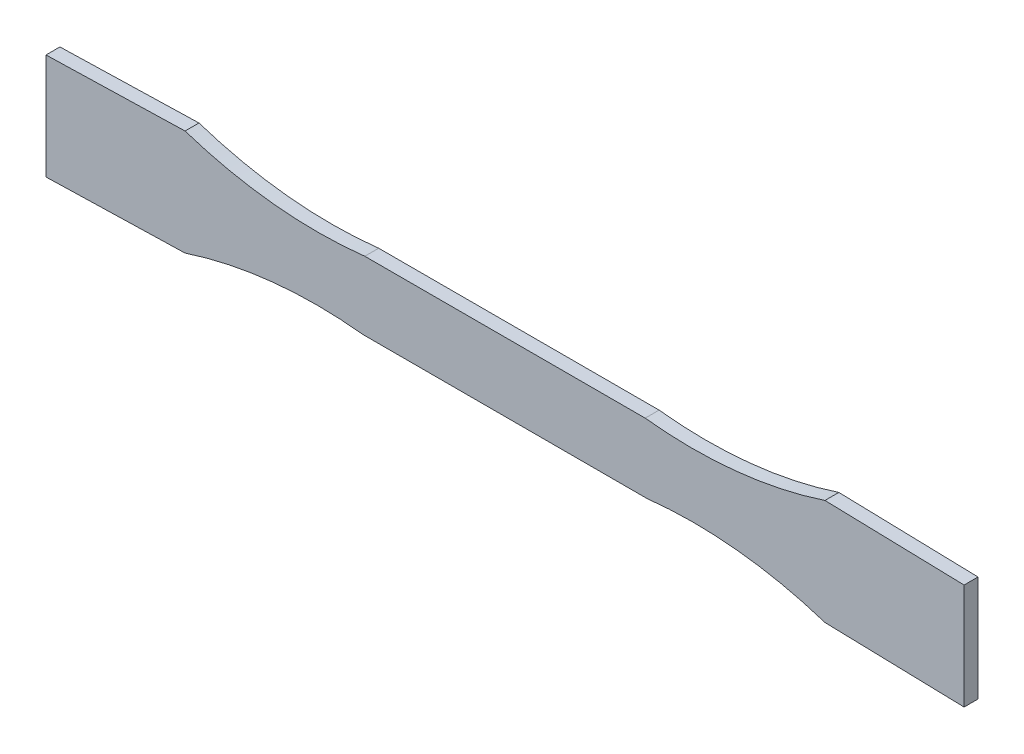
SolidWorks part; units mm, degrees
ref_plane "Front Plane" through (0, 0, 0) normal (0, 0, 1) x (1, 0, 0)
ref_plane "Top Plane" through (0, 0, 0) normal (0, 1, 0) x (1, 0, 0)
ref_plane "Right Plane" through (0, 0, 0) normal (1, 0, 0) x (0, 0, -1)
sketch "Sketch2" plane through (0, 0, 0) normal (0, 0, 1) x (1, 0, 0)
  line L0 (-46.6281, 0) -> (118.3719, 0) construction
  line L9 (-46.6174, 8.5394) -> (-46.6174, -10.4606)
  line L19 (-46.6174, -10.4606) -> (-21.626, -9.8028)
  line L21 (-46.6174, 8.5394) -> (-46.6174, -10.4606)
  line L22 (-46.6174, 8.5394) -> (-21.626, 9.1972)
  line L23 (10.676, 5.8556) -> (61.0678, 5.8556)
  line L24 (10.3532, -6.4946) -> (61.3906, -6.4946)
  line L25 (118.3826, 8.5394) -> (118.3826, -10.4606)
  line L26 (118.3826, -10.4606) -> (93.3913, -9.8028)
  line L27 (118.3826, 8.5394) -> (93.374, 9.1972)
  arc A0 (-21.626, 9.1972) -> (10.676, 5.8556) centre (2.1647, 81.3775) ccw
  arc A1 (-21.626, -9.8028) -> (10.3532, -6.4946) centre (2.007, -82.0349) cw
  arc A6 (93.3913, -9.8028) -> (61.3906, -6.4946) centre (69.7528, -82.0331) ccw
  arc A7 (93.374, 9.1972) -> (61.0678, 5.8556) centre (69.5821, 81.3772) cw
  point P14 (35.8719, -6.4946)
  point P18 (35.8719, 5.8556)
  dimension "D3" = 76
  dimension "D1" = 76
  dimension "D4" = 25
  dimension "D9" = 76
  dimension "D10" = 76
  dimension "D2" = 165
  dimension "D5" = 19
  dimension "D6" = 115
  dimension "D7" = 165
  dimension "D8" = 19
extrude "Boss-Extrude2" add sketch "Sketch2" along normal blind 2.5
